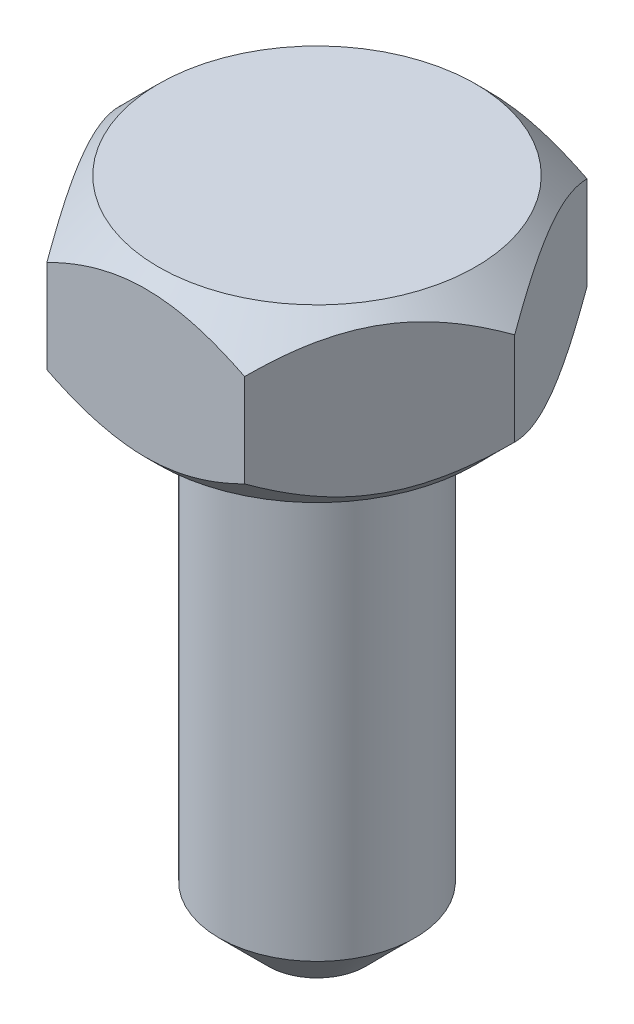
SolidWorks part; units mm, degrees
ref_plane "Спереди" through (0, 0, 0) normal (0, 0, 1) x (1, 0, 0)
ref_plane "Сверху" through (0, 0, 0) normal (0, 1, 0) x (1, 0, 0)
ref_plane "Справа" through (0, 0, 0) normal (1, 0, 0) x (0, 0, -1)
sketch "Эскиз1" plane through (0, 0, 0) normal (0, 1, 0) x (1, 0, 0)
  line L0 (-2.0207, 3.5) -> (2.0207, 3.5)
  line L1 (2.0207, 3.5) -> (4.0415, 0)
  line L2 (4.0415, 0) -> (2.0207, -3.5)
  line L3 (2.0207, -3.5) -> (-2.0207, -3.5)
  line L4 (-2.0207, -3.5) -> (-4.0415, 0)
  line L5 (-4.0415, 0) -> (-2.0207, 3.5)
  dimension "D5" = 3.5
  dimension "D2" = 120
  dimension "D3" = 120
  dimension "D4" = 120
  dimension "D6" = 3.5
  dimension "D7" = 3.5
  dimension "D8" = 3.5
  dimension "D9" = 3.5
  dimension "D10" = 120
  dimension "D11" = 3.5
extrude "Вытянуть1" add sketch "Эскиз1" against normal blind 3.5
sketch "Эскиз5" plane through (0, -3.5, 0) normal (0, -1, 0) x (1, 0, 0)
  circle A0 centre (0, 0) radius 2
  dimension "D1" = 4
extrude "Вытянуть2" add sketch "Эскиз5" along normal blind 10
chamfer "Фаска1" distance 1 angle 45 1 edges at (0, -13.5, -2)
ref_axis "Ось1" through (0, -3.5, 0) along (0, -1, 0)
ref_plane "Плоскость1" through (0, 0, 0) normal (0, 0, 1) x (1, 0, 0)
sketch "Эскиз4" plane through (0, 0, 0) normal (0, 0, 1) x (1, 0, 0)
  line L0 (-4.0415, -0.8) -> (-3.2415, 0)
  line L1 (-4.0415, -3.5) -> (-4.0415, 0) construction
  line L2 (-4.0415, 0) -> (-2.0207, 0) construction
  line L3 (-3.2415, 0) -> (-4.0415, 0)
  line L4 (-4.0415, 0) -> (-4.0415, -0.8)
  line L5 (-4.0415, -2.7) -> (-3.2415, -3.5)
  line L6 (-4.0415, -3.5) -> (-2.0207, -3.5) construction
  line L7 (-3.2415, -3.5) -> (-4.0415, -3.5)
  line L8 (-4.0415, -3.5) -> (-4.0415, -2.7)
  dimension "D1" = 0.8
  dimension "D2" = 0.8
  dimension "D3" = 0.8
  dimension "D4" = 0.8
revolve "Вырез-Повернуть1" cut sketch "Эскиз4" angle 360 about axis through (0, -3.5, 0) along (0, -1, 0)
